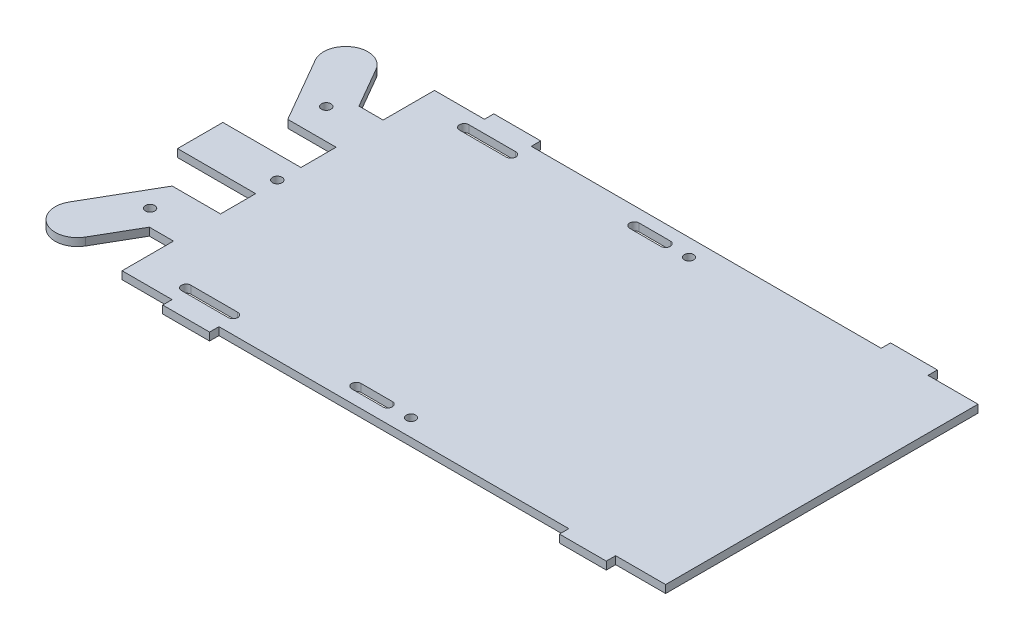
SolidWorks part; units mm, degrees
ref_plane "Front Plane" through (0, 0, 0) normal (0, 0, 1) x (1, 0, 0)
ref_plane "Top Plane" through (0, 0, 0) normal (0, 1, 0) x (1, 0, 0)
ref_plane "Right Plane" through (0, 0, 0) normal (1, 0, 0) x (0, 0, -1)
sketch "Sketch1" plane through (0, 0, 0) normal (0, 1, 0) x (1, 0, 0)
  line L0 (-87, -50) -> (-87, -7.25)
  line L1 (-87, 50) -> (87, 50)
  line L2 (87, 50) -> (87, -50)
  line L3 (87, -50) -> (-87, -50)
  line L4 (0, 0) -> (-141.4802, 0) construction
  line L6 (-87, 7.25) -> (-112, 7.25)
  line L7 (-112, 7.25) -> (-112, -7.25)
  line L8 (-112, -7.25) -> (-87, -7.25)
  line L9 (-87, 7.25) -> (-87, 50)
  point P3 (-87, 0)
  point P6 (0, 50)
  dimension "D1" = 174
  dimension "D2" = 100
  dimension "D3" = 14.5
  dimension "D4" = 25
  dimension "D5" = 42.75
extrude "Boss-Extrude1" add sketch "Sketch1" along normal blind 2.5
sketch "Sketch2" plane through (0, 0, 50) normal (0, 0, 1) x (1, 0, 0)
  line L0 (-71, 1.25) -> (-56, 1.25) construction
  line L1 (-71, 2.5) -> (-56, 2.5)
  line L2 (-71, 0) -> (-56, 0)
  line L3 (-87, 2.5) -> (87, 2.5) construction
  line L4 (0, 0) -> (0, 14.7074) construction
  line L5 (71, 1.25) -> (56, 1.25) construction
  line L6 (71, 2.5) -> (56, 2.5)
  line L7 (71, 0) -> (56, 0)
  line L8 (-71, 0) -> (-71, 2.5)
  line L9 (-56, 0) -> (-56, 2.5)
  line L10 (56, 0) -> (56, 2.5)
  line L11 (71, 0) -> (71, 2.5)
  line L12 (-87, 0) -> (87, 0) construction
  arc A0 (-71, 2.5) -> (-71, 0) centre (-71, 1.25) ccw
  arc A1 (-56, 0) -> (-56, 2.5) centre (-56, 1.25) ccw
  arc A2 (71, 2.5) -> (71, 0) centre (71, 1.25) cw
  arc A3 (56, 0) -> (56, 2.5) centre (56, 1.25) cw
  point P2 (-63.5, 1.25)
  point P7 (-63.5, 2.5)
  point P18 (63.5, 1.25)
  point P31 (-63.5, 0)
  line M6 (-87, 0) -> (87, 0)
  line M8 (87, 2.5) -> (-87, 2.5)
  dimension "D1" = 15
  dimension "D2" = 16
extrude "Boss-Extrude2" add sketch "Sketch2" along normal blind 3 contours L9 L8 M6 M8 | L11 L10 M6 M8
mirror "Mirror1" about plane through (0, 0, 0) normal (0, 0, 1) of "Boss-Extrude2"
sketch "Sketch5" plane through (0, 2.5, 0) normal (0, 1, 0) x (1, 0, 0)
  line L1 (-102.2048, -46.5023) -> (-94.7291, -33.554)
  line L2 (-118.0791, -45.5495) -> (-102.4581, -18.4931) construction
  line L5 (-114.5231, -39.3903) -> (-102.4581, -18.4931)
  line L6 (-102.4581, -18.4931) -> (-87, -18.4931)
  line L7 (-94.7291, -33.554) -> (-87, -33.554)
  line L10 (-114.5231, -39.3903) -> (-102.2048, -46.5023) construction
  line L11 (-87, -7.25) -> (-87, -50) construction
  line L13 (-87, -33.554) -> (-87, -18.4931)
  arc A0 (-114.5231, -39.3903) -> (-102.2048, -46.5023) centre (-108.3639, -42.9463) ccw
  circle A1 centre (-99.8549, -28.2083) radius 1.524 construction
  circle A2 centre (-99.8549, -28.2083) radius 1.524
  point P12 (-108.3639, -42.9463)
  dimension "D1" = 15.0609
extrude "Boss-Extrude4" add sketch "Sketch5" against normal blind 2.5
sketch "Sketch6" plane through (0, 0, 0) normal (0, -1, 0) x (1, 0, 0)
  circle A0 centre (-87.3188, 0) radius 1.524
extrude "Cut-Extrude1" cut sketch "Sketch6" against normal blind 2.5
mirror "Mirror2" about plane through (0, 0, 0) normal (0, 0, 1) of "Boss-Extrude4"
sketch "Sketch7" plane through (0, 2.5, 0) normal (0, 1, 0) x (1, 0, 0)
  line L1 (-45, 40) -> (30, 40)
  line L2 (-45, 40) -> (-45, -40)
  line L3 (-45, -40) -> (30, -40)
  line L4 (30, 40) -> (30, -40)
  line L5 (-82, 40) -> (-47, 40)
  line L6 (-82, 40) -> (-82, -40)
  line L7 (-82, -40) -> (-47, -40)
  line L8 (-47, 40) -> (-47, -40)
  line L13 (-72, 44.5) -> (-57, 44.5) construction
  line L14 (-72, 46) -> (-57, 46)
  line L15 (-72, 43) -> (-57, 43)
  line L16 (-1.0102, 0) -> (-29.6242, 0) construction
  line L17 (-87, -33.554) -> (-87, -50) construction
  line L18 (-72, -44.5) -> (-57, -44.5) construction
  line L19 (-72, -46) -> (-57, -46)
  line L20 (-72, -43) -> (-57, -43)
  line L21 (-57, -44.5) -> (20.5719, -44.5) construction
  line L22 (-17.5, -44.5) -> (-7.5, -44.5) construction
  line L23 (-17.5, -43) -> (-7.5, -43)
  line L24 (-17.5, -46) -> (-7.5, -46)
  line L25 (-17.5, 44.5) -> (-7.5, 44.5) construction
  line L26 (-17.5, 43) -> (-7.5, 43)
  line L27 (-17.5, 46) -> (-7.5, 46)
  line L28 (-7.5, 44.5) -> (87, 44.5) construction
  line L29 (87, -50) -> (87, 50) construction
  arc A0 (-72, 46) -> (-72, 43) centre (-72, 44.5) ccw
  arc A1 (-57, 43) -> (-57, 46) centre (-57, 44.5) ccw
  arc A2 (-72, -46) -> (-72, -43) centre (-72, -44.5) cw
  arc A3 (-57, -43) -> (-57, -46) centre (-57, -44.5) cw
  arc A4 (-17.5, -43) -> (-17.5, -46) centre (-17.5, -44.5) ccw
  arc A5 (-7.5, -46) -> (-7.5, -43) centre (-7.5, -44.5) ccw
  arc A6 (-17.5, 43) -> (-17.5, 46) centre (-17.5, 44.5) cw
  arc A7 (-7.5, 46) -> (-7.5, 43) centre (-7.5, 44.5) cw
  circle A10 centre (0, 44.5) radius 1.5
  circle A11 centre (0, -44.5) radius 1.5
  point P8 (-47, 0)
  point P10 (30, 0)
  point P13 (-64.5, 44.5)
  point P22 (-64.5, 40)
  point P27 (-64.5, -44.5)
  point P35 (-12.5, -44.5)
  point P41 (-7.5, -40)
  point P44 (-12.5, 44.5)
  dimension "D12" = 3
  dimension "D1" = 35
  dimension "D2" = 80
  dimension "D3" = 80
  dimension "D4" = 75
  dimension "D5" = 3
  dimension "D6" = 15
  dimension "D7" = 5
  dimension "D8" = 3
  dimension "D9" = 2
  dimension "D10" = 3
  dimension "D11" = 10
extrude "Cut-Extrude2" cut sketch "Sketch7" against normal blind 2.5 contours A3 L20 A2 L19 | L24 A5 L23 A4 | L15 A1 L14 A0 | A7 L27 A6 L26 | A10 | A11
